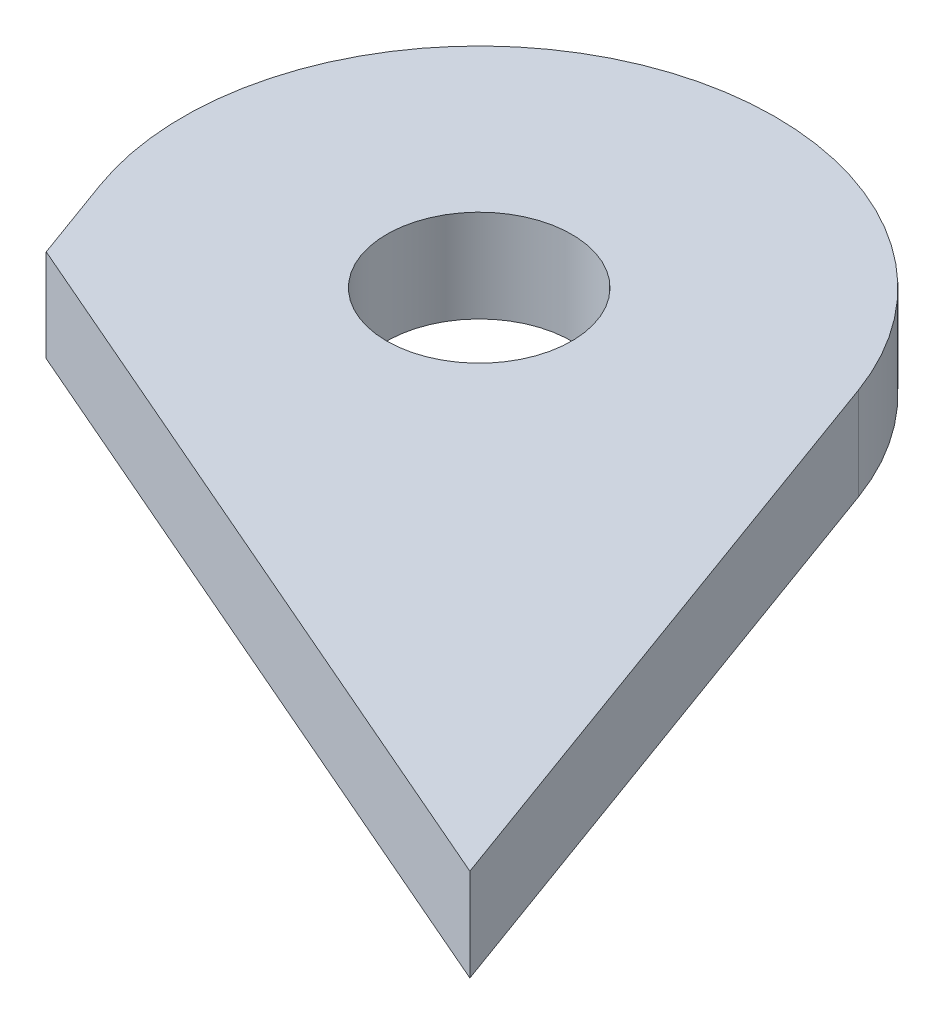
SolidWorks part; units mm, degrees
material "Plain Carbon Steel"
ref_plane "Front Plane" through (0, 0, 0) normal (0, 0, 1) x (1, 0, 0)
ref_plane "Top Plane" through (0, 0, 0) normal (0, 1, 0) x (1, 0, 0)
ref_plane "Right Plane" through (0, 0, 0) normal (1, 0, 0) x (0, 0, -1)
sketch "Sketch1" plane through (0, 0, 0) normal (0, 1, 0) x (1, 0, 0)
  line L5 (19.0946, 6.9498) -> (-22.2251, -8.0893) construction
  line L6 (19.0946, 6.9498) -> (34.3655, -35.0068)
  line L7 (-968.2745, -35.0068) -> (49031.7255, -35.0068) construction
  line L8 (34.3655, -35.0068) -> (-16.9909, -12.7296)
  line L9 (-19.0946, -6.9498) -> (-16.9909, -12.7296)
  circle A2 centre (0, 0) radius 6.35
  arc A4 (19.0946, 6.9498) -> (-19.0946, -6.9498) centre (0, 0) ccw
  point P3 (8.6873, -23.8682)
  dimension "D1" = 12.7
  dimension "D2" = 13.97
  dimension "D3" = 70
  dimension "D4" = 23.45
  dimension "D5" = 25.4
extrude "Boss-Extrude1" add sketch "Sketch1" along normal blind 6.35
